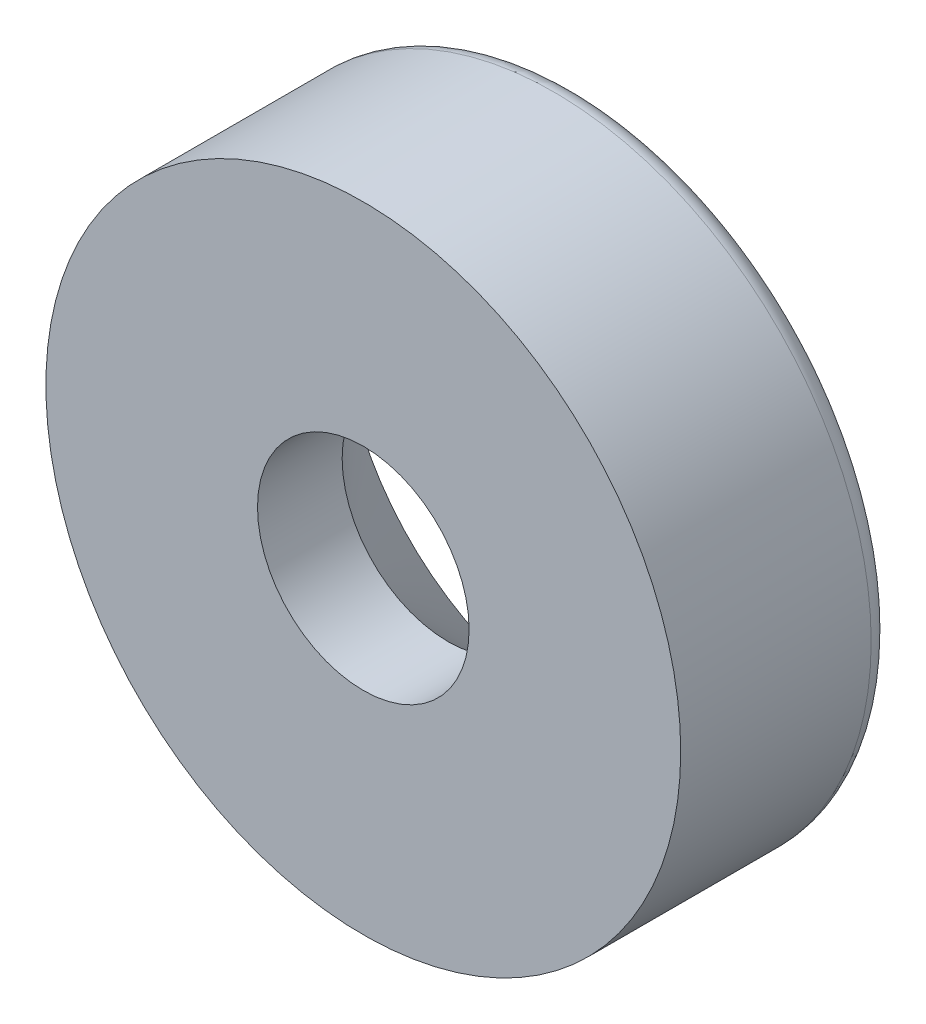
SolidWorks part; units mm, degrees
ref_plane "前视基准面" through (0, 0, 0) normal (0, 0, 1) x (1, 0, 0)
ref_plane "上视基准面" through (0, 0, 0) normal (0, 1, 0) x (1, 0, 0)
ref_plane "右视基准面" through (0, 0, 0) normal (1, 0, 0) x (0, 0, -1)
sketch "草图1" plane through (0, 0, 0) normal (0, 0, 1) x (1, 0, 0)
  circle A0 centre (0, 0) radius 3
  circle A1 centre (0, 0) radius 1
extrude "凸台-拉伸1" add sketch "草图1" along normal blind 2
chamfer "倒角1" distance 1.2 angle 45 1 edges at (1, 0, 0)
fillet "圆角1" radius 0.2 1 edges at (3, 0, 0)
